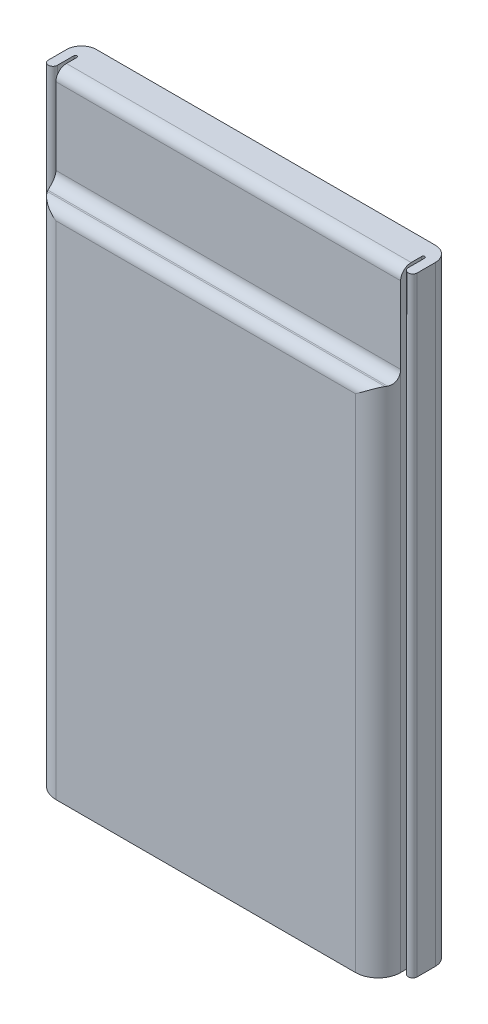
SolidWorks part; units mm, degrees
ref_plane "Front" through (0, 0, 0) normal (0, 0, 1) x (1, 0, 0)
ref_plane "Top" through (0, 0, 0) normal (0, 1, 0) x (1, 0, 0)
ref_plane "Right" through (0, 0, 0) normal (1, 0, 0) x (0, 0, -1)
sketch "Эскиз1" plane through (0, 0, 0) normal (0, 1, 0) x (1, 0, 0)
  line L0 (-11.25, 0) -> (11.25, 0)
  line L1 (-9.95, -4) -> (9.95, -4)
  line L2 (-12.25, -1) -> (-12.25, -2.2)
  line L3 (12.25, -1) -> (12.25, -2.2)
  line L4 (-11.45, -2.5) -> (-11.45, -1.1)
  line L5 (11.45, -1.1) -> (11.45, -2.5)
  line L6 (11.65, -2.2) -> (11.65, -1.1)
  line L7 (-11.65, -2.2) -> (-11.65, -1.1)
  arc A0 (-11.25, 0) -> (-12.25, -1) centre (-11.25, -1) ccw
  arc A1 (11.25, 0) -> (12.25, -1) centre (11.25, -1) cw
  arc A2 (-11.45, -2.5) -> (-9.95, -4) centre (-9.95, -2.5) ccw
  arc A3 (11.45, -2.5) -> (9.95, -4) centre (9.95, -2.5) cw
  arc A4 (12.25, -2.2) -> (11.65, -2.2) centre (11.95, -2.2) cw
  arc A5 (11.45, -1.1) -> (11.65, -1.1) centre (11.55, -1.1) cw
  arc A6 (-12.25, -2.2) -> (-11.65, -2.2) centre (-11.95, -2.2) ccw
  arc A7 (-11.45, -1.1) -> (-11.65, -1.1) centre (-11.55, -1.1) ccw
  point P20 (11.55, -1)
  point P21 (11.95, -2.5)
  point P27 (-11.55, -1)
  point P28 (-11.95, -2.5)
  dimension "D1" = 24.5
  dimension "D3" = 1.5
  dimension "D4" = 1
  dimension "D5" = 0.3
  dimension "D6" = 0.1
  dimension "D2" = 4
extrude "Бобышка-Вытянуть1" add sketch "Эскиз1" along normal mid plane 40.5
sketch "Эскиз2" plane through (0, 0, 0) normal (1, 0, 0) x (0, 0, -1)
  line L0 (-2.5, 19.55) -> (-2.5, 14.45)
  line L1 (-3.2, 13.75) -> (-3.3, 13.75)
  line L2 (-4, 20.25) -> (-4, 13.05)
  line L3 (-4, 20.25) -> (-4, -20.25) construction
  line L6 (-4, 20.25) -> (-1.8, 20.25)
  line L7 (0, 20.25) -> (-1, 20.25) construction
  arc A0 (-2.5, 14.45) -> (-3.2, 13.75) centre (-3.2, 14.45) cw
  arc A1 (-3.3, 13.75) -> (-4, 13.05) centre (-3.3, 13.05) ccw
  arc A2 (-1.8, 20.25) -> (-2.5, 19.55) centre (-1.8, 19.55) ccw
  dimension "D1" = 0.7
  dimension "D2" = 2.5
  dimension "D3" = 6.5
extrude "Вырез-Вытянуть1" cut sketch "Эскиз2" against normal up to next and the other way up to next
